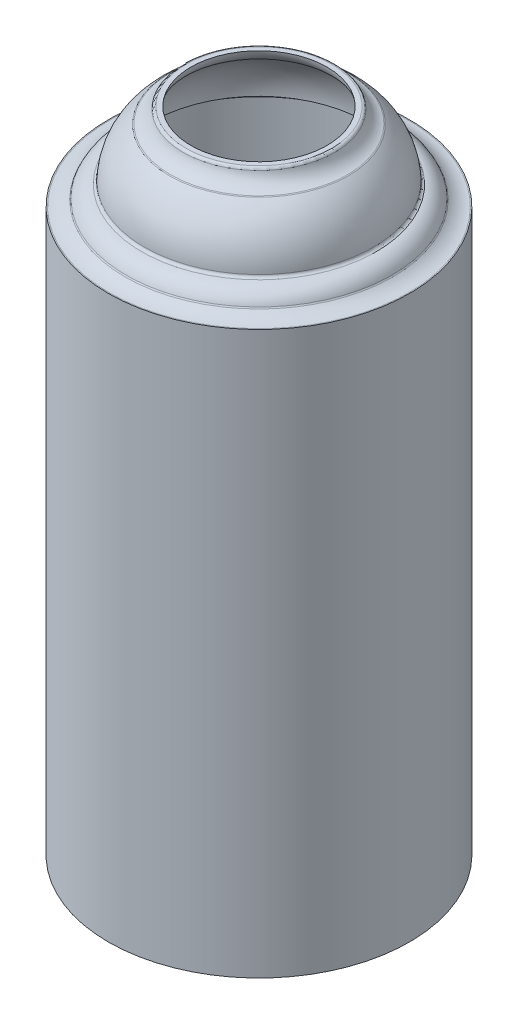
SolidWorks part; units mm, degrees
ref_plane "Front Plane" through (0, 0, 0) normal (0, 0, 1) x (1, 0, 0)
ref_plane "Top Plane" through (0, 0, 0) normal (0, 1, 0) x (1, 0, 0)
ref_plane "Right Plane" through (0, 0, 0) normal (1, 0, 0) x (0, 0, -1)
sketch "Sketch1" plane through (0, 0, 0) normal (0, 1, 0) x (1, 0, 0)
  circle A0 centre (0, 0) radius 66.04
  circle A1 centre (0, 0) radius 64.4525
  dimension "D1" = 132.08
  dimension "D2" = 128.905
extrude "Boss-Extrude1" add sketch "Sketch1" along normal blind 246.38
sketch "Sketch4" plane through (0, 0, 0) normal (0, 0, 1) x (1, 0, 0)
  line L0 (66.04, 246.38) -> (-66.04, 246.38) construction
  line L2 (0, 246.38) -> (0, 284.48)
  line L3 (0, 284.48) -> (-33.02, 284.48)
  line L4 (-33.02, 284.48) -> (-33.02, 277.7864) construction
  line L5 (-33.02, 277.7864) -> (-39.0116, 277.7864) construction
  line L6 (-39.0116, 277.7864) -> (-39.0116, 254.9621) construction
  line L7 (-39.0116, 254.9621) -> (-50.3137, 254.9621) construction
  line L8 (-50.3137, 254.9621) -> (-50.3137, 246.38) construction
  line L10 (-66.04, 246.38) -> (-66.04, 0) construction
  line L11 (-66.04, 246.38) -> (0, 246.38)
  arc A0 (-50.3137, 254.9621) -> (-39.0116, 277.7864) centre (-21.6164, 254.9621) cw
  arc A1 (-50.3137, 254.9621) -> (-58.4248, 249.1841) centre (-50.3137, 246.38) ccw
  arc A2 (-33.02, 284.48) -> (-39.0116, 277.7864) centre (-40.9686, 285.5665) cw
  arc A3 (-58.4248, 249.1841) -> (-66.04, 246.38) centre (-65.8112, 257.5011) cw
  point P3 (0, 246.38)
  point P10 (0, 284.48)
  dimension "D3" = 8.0225
  dimension "D4" = 28.6973
  dimension "D5" = 8.5821
  dimension "D6" = 11.1234
  dimension "D7" = 22.8242
  dimension "D1" = 38.1
  dimension "D2" = 33.02
  dimension "D8" = 5.9916
revolve "Revolve5" add sketch "Sketch4" angle 360 about L2
fillet "Fillet3" radius 1.27 5 edges at (0, 284.48, -33.02) (0, 277.7864, -39.0116) (0, 254.9621, -50.3137) (0, 249.1841, -58.4248) (0, 246.38, -65.5824)
sketch "Sketch7" plane through (0, 0, 0) normal (1, 0, 0) x (0, 0, -1)
  line L0 (-66.04, 0) -> (0, 0)
  line L1 (-66.04, 0) -> (-66.04, 3.175)
  line L2 (-66.04, 246.38) -> (-66.04, 0) construction
  line L3 (0, 21.6959) -> (0, 18.5209)
  line L5 (0, 0) -> (0, 21.6959) construction
  arc A0 (-66.04, 0) -> (0, 18.5209) centre (0, -108.4791) cw
  arc A1 (-66.04, 3.175) -> (0, 21.6959) centre (0, -105.3041) cw
  dimension "D1" = 127
  dimension "D4" = 3.175
  dimension "D6" = 127
  dimension "D2" = 3.175
  dimension "D3" = 3.175
  dimension "D5" = 21.6959
revolve "Revolve8" add sketch "Sketch7" angle 360 about L5
sketch "Sketch10" plane through (0, 0, 0) normal (0, 0, 1) x (1, 0, 0)
  line L0 (66.04, 246.38) -> (-66.04, 246.38) construction
  line L2 (0, 246.38) -> (0, 284.48)
  line L3 (0, 284.48) -> (-29.845, 284.48)
  line L4 (-29.845, 284.48) -> (-29.845, 277.7864) construction
  line L5 (-29.845, 277.7864) -> (-35.8366, 277.7864) construction
  line L6 (-35.8366, 277.7864) -> (-35.8366, 254.9621) construction
  line L7 (-35.8366, 254.9621) -> (-47.1387, 254.9621) construction
  line L8 (-47.1387, 254.9621) -> (-47.1387, 246.38) construction
  line L11 (-66.04, 246.38) -> (0, 246.38)
  arc A0 (-47.1387, 254.9621) -> (-35.8366, 277.7864) centre (-18.4414, 254.9621) cw
  arc A1 (-47.1387, 254.9621) -> (-55.2498, 249.1841) centre (-47.1387, 246.38) ccw
  arc A2 (-29.845, 284.48) -> (-35.8366, 277.7864) centre (-37.7936, 285.5665) cw
  arc A3 (-55.2498, 249.1841) -> (-66.04, 246.38) centre (-63.066, 257.0985) cw
  point P3 (0, 246.38)
  point P10 (0, 284.48)
  dimension "D3" = 8.0225
  dimension "D4" = 28.6973
  dimension "D5" = 8.5821
  dimension "D6" = 11.1234
  dimension "D7" = 22.8242
  dimension "D1" = 38.1
  dimension "D2" = 29.845
  dimension "D8" = 5.9916
revolve "Cut-Revolve1" cut sketch "Sketch10" angle 360 about L2
